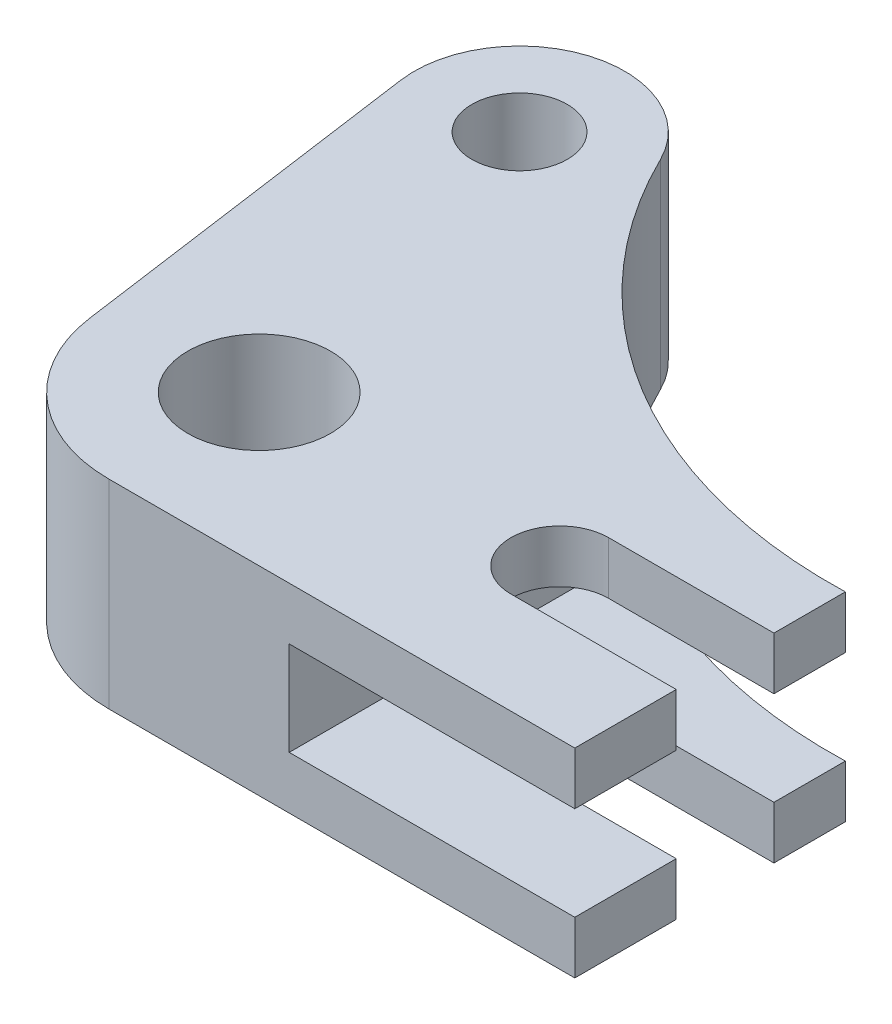
SolidWorks part; units mm, degrees
material "AISI 1020"
ref_plane "Front Plane" through (0, 0, 0) normal (0, 0, 1) x (1, 0, 0)
ref_plane "Top Plane" through (0, 0, 0) normal (0, 1, 0) x (1, 0, 0)
ref_plane "Right Plane" through (0, 0, 0) normal (1, 0, 0) x (0, 0, -1)
sketch "Sketch1" plane through (0, 0, 0) normal (0, 1, 0) x (1, 0, 0)
  line L0 (0, 0) -> (-62, 0)
  line L1 (-62, 0) -> (-62, 20) construction
  line L2 (-62, 20) -> (-62, 43.1453) construction
  line L3 (-62, 20) -> (-74.6821, 67.3304) construction
  line L4 (-88.547, 65.39) -> (-81.807, 17.2281)
  line L5 (0, 36) -> (0, 103) construction
  line L6 (-22, 26.5) -> (0, 26.5)
  line L7 (-22, 13.5) -> (0, 13.5)
  line L8 (0, 0) -> (0, 13.5)
  line L9 (0, 26.5) -> (0, 36)
  circle A0 centre (-62, 20) radius 9.5
  circle A1 centre (-74.6821, 67.3304) radius 6.35
  arc A2 (-81.807, 17.2281) -> (-62, 0) centre (-62, 20) ccw
  arc A3 (-62.1103, 73.4906) -> (-88.547, 65.39) centre (-74.6821, 67.3304) ccw
  arc A4 (-22, 26.5) -> (-22, 13.5) centre (-22, 20) ccw
  arc A5 (-62.1103, 73.4906) -> (0, 36) centre (-1.945, 102.9718) ccw
  point P13 (0, 20)
  dimension "D3" = 19
  dimension "D6" = 12.7
  dimension "D7" = 28
  dimension "D8" = 20
  dimension "D10" = 6.5
  dimension "D17" = 134
  dimension "D1" = 62
  dimension "D2" = 20
  dimension "D4" = 15
  dimension "D5" = 49
  dimension "D9" = 22
  dimension "D11" = 36
  dimension "D12" = 13.5
  dimension "D13" = 26.5
  dimension "D14" = 22
  dimension "D15" = 9.5
  dimension "D16" = 67
extrude "Boss-Extrude1" add sketch "Sketch1" along normal mid plane 26.5
sketch "Sketch2" plane through (0, 0, 0) normal (1, 0, 0) x (0, 0, -1)
  line L0 (0, 13.25) -> (0, -13.25) construction
  line L7 (0, -6.25) -> (0, 6.25)
  line L8 (0, 6.25) -> (73.3389, 6.25)
  line L9 (73.3389, 6.25) -> (73.3389, -6.25)
  line L10 (73.3389, -6.25) -> (0, -6.25)
  line L11 (0, -13.25) -> (13.5, -13.25) construction
  line L12 (0, 13.25) -> (13.5, 13.25) construction
  dimension "D1" = 7
  dimension "D2" = 7
  dimension "D3" = 73.3389
extrude "Cut-Extrude3" cut sketch "Sketch2" against normal blind 38 contours L8 L9 L10 L7
equation "\"A\"= 62mm"
equation "\"B\"= 20mm"
equation "\"C\"= 26.50mm"
